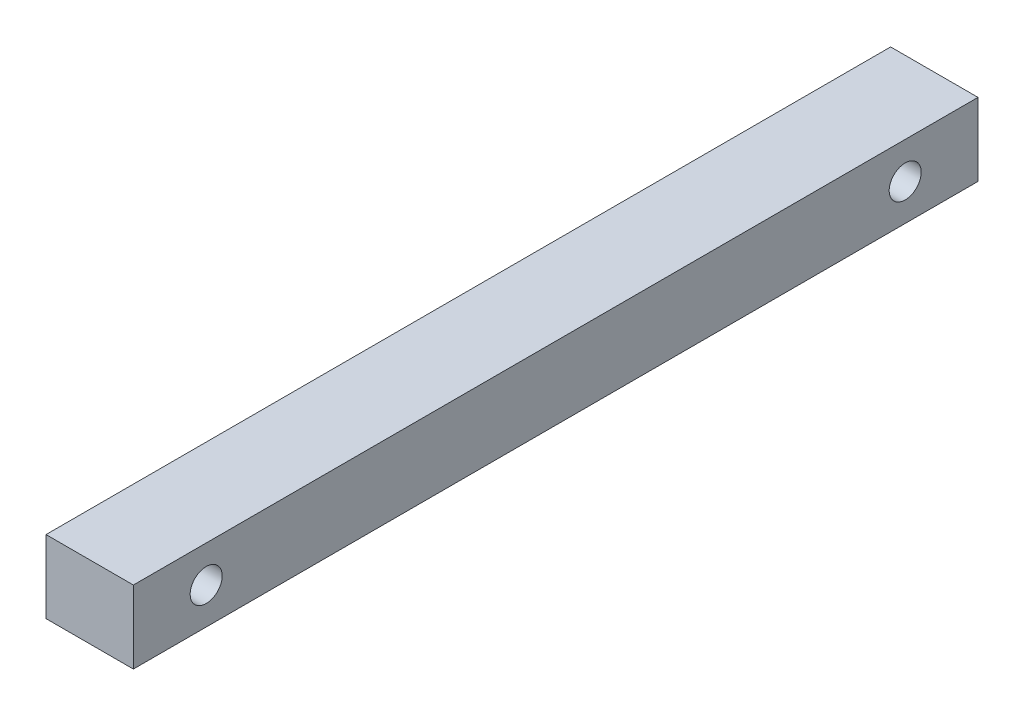
SolidWorks part; units mm, degrees
ref_plane "Plano frontal" through (0, 0, 0) normal (0, 0, 1) x (1, 0, 0)
ref_plane "Plano superior" through (0, 0, 0) normal (0, 1, 0) x (1, 0, 0)
ref_plane "Plano direito" through (0, 0, 0) normal (1, 0, 0) x (0, 0, -1)
sketch "Esboço1" plane through (0, 0, 0) normal (0, 0, 1) x (1, 0, 0)
  line L5 (15, -12.5) -> (-15, -12.5)
  line L6 (15, -12.5) -> (15, 12.5)
  line L11 (15, 12.5) -> (-15, 12.5)
  line L12 (-15, -12.5) -> (-15, 12.5)
  line L13 (15, -12.5) -> (-15, 12.5) construction
  line L14 (15, 12.5) -> (-15, -12.5) construction
  point P0 (0, 0)
  dimension "D1" = 25
  dimension "D2" = 30
extrude "Ressalto-extrusão2" add sketch "Esboço1" along normal blind 290
sketch "Esboço2" plane through (-15, 0, 0) normal (-1, 0, 0) x (0, 0, 1)
  line L0 (0, 0) -> (25, 0)
  line L1 (280.9096, 5.6742) -> (290, 0)
  line L2 (290, 12.5) -> (290, -12.5) construction
  line L3 (290, 0) -> (270, 0)
  line L4 (270, 0) -> (265, 0)
  circle A0 centre (25, 0) radius 5.5
  circle A1 centre (265, 0) radius 5.5
  dimension "D2" = 11
  dimension "D5" = 11
  dimension "D1" = 25
  dimension "D3" = 20
  dimension "D4" = 5
extrude "Corte-extrusão1" cut sketch "Esboço2" against normal blind 290
